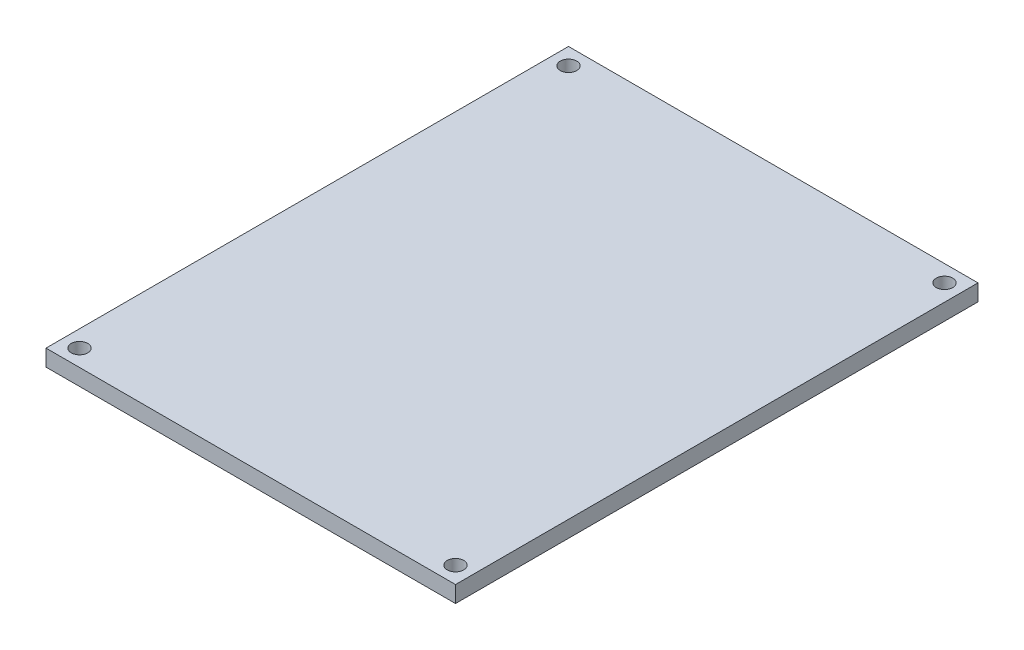
SolidWorks part; units mm, degrees
material "A-玻璃纤维"
ref_plane "前视基准面" through (0, 0, 0) normal (0, 0, 1) x (1, 0, 0)
ref_plane "上视基准面" through (0, 0, 0) normal (0, 1, 0) x (1, 0, 0)
ref_plane "右视基准面" through (0, 0, 0) normal (1, 0, 0) x (0, 0, -1)
other "Configuration Table"
sketch "草图1" plane through (0, 0, 0) normal (0, 1, 0) x (1, 0, 0)
  line L0 (0, 0) -> (59.2167, 0) construction
  line L1 (-37.28, -47.565) -> (37.28, -47.565)
  line L2 (-37.28, -47.565) -> (-37.28, 47.565)
  line L3 (-37.28, 47.565) -> (37.28, 47.565)
  line L4 (37.28, -47.565) -> (37.28, 47.565)
  line L5 (-37.28, -47.565) -> (37.28, 47.565) construction
  line L6 (-37.28, 47.565) -> (37.28, -47.565) construction
  line L7 (0, 0) -> (0, 79.8198) construction
  circle A0 centre (-34.225, 44.515) radius 1.5
  circle A1 centre (34.225, 44.515) radius 1.5
  circle A2 centre (34.225, -44.515) radius 1.5
  circle A3 centre (-34.225, -44.515) radius 1.5
  point P0 (0, 0)
  dimension "D3" = 3
  dimension "D4" = 68.45
  dimension "D5" = 89.03
  dimension "D1" = 74.56
  dimension "D2" = 95.13
extrude "凸台-拉伸1" add sketch "草图1" along normal blind 3
